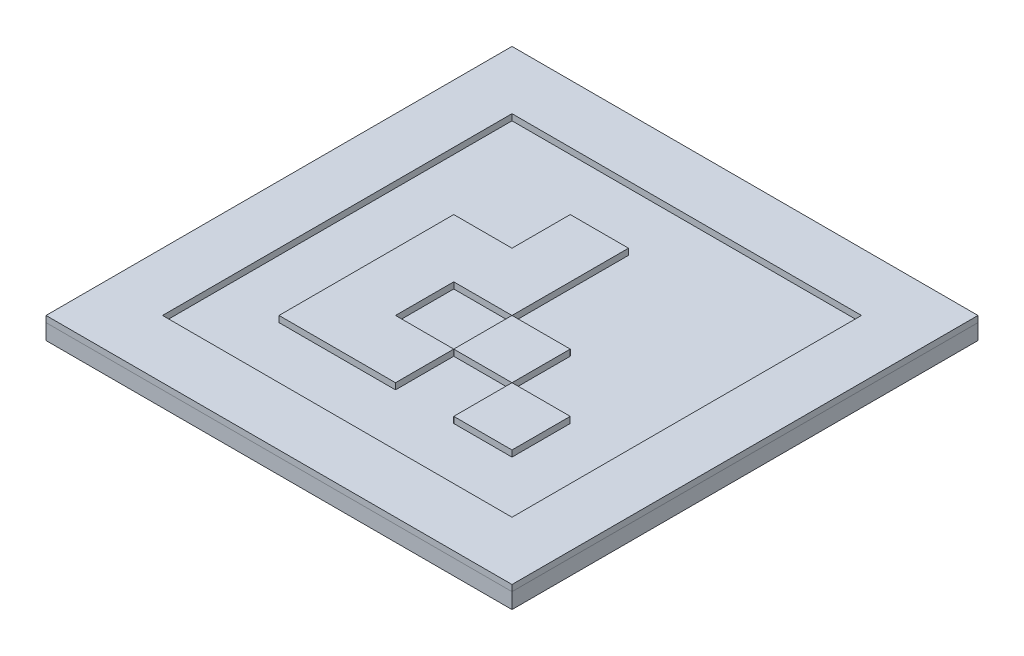
SolidWorks part; units mm, degrees
ref_plane "Спереди" through (0, 0, 0) normal (0, 0, 1) x (1, 0, 0)
ref_plane "Сверху" through (0, 0, 0) normal (0, 1, 0) x (1, 0, 0)
ref_plane "Справа" through (0, 0, 0) normal (1, 0, 0) x (0, 0, -1)
sketch "Эскиз1" plane through (0, 0, 0) normal (0, 1, 0) x (1, 0, 0)
  line L1 (-75, -75) -> (75, -75)
  line L2 (-75, -75) -> (-75, 75)
  line L3 (-75, 75) -> (75, 75)
  line L4 (75, -75) -> (75, 75)
  line L5 (-75, -75) -> (75, 75) construction
  line L6 (-75, 75) -> (75, -75) construction
  point P0 (0, 0)
  dimension "D1" = 150
extrude "Бобышка-Вытянуть1" add sketch "Эскиз1" along normal blind 5
sketch "Эскиз10" plane through (0, 5, 0) normal (0, 1, 0) x (1, 0, 0)
  line L0 (37.5, -37.5) -> (37.5, 37.5)
  line L1 (37.5, 37.5) -> (-37.5, 37.5)
  line L2 (-37.5, 37.5) -> (-37.5, -37.5)
  line L3 (-37.5, -37.5) -> (37.5, -37.5)
  line L4 (75, -75) -> (75, 75)
  line L5 (75, 75) -> (-75, 75)
  line L6 (-75, 75) -> (-75, -75)
  line L7 (-75, -75) -> (75, -75)
  line L8 (75, -75) -> (75, 75) construction
  line L9 (75, 75) -> (-75, 75) construction
  line L10 (-75, 75) -> (-75, -75) construction
  line L11 (-75, -75) -> (75, -75) construction
  line L12 (-18.75, 37.5) -> (-18.75, 18.75)
  line L13 (-37.5, 37.5) -> (-18.75, 37.5)
  line L14 (-37.5, 37.5) -> (-37.5, 18.75)
  line L15 (-37.5, 18.75) -> (-18.75, 18.75)
  line L16 (56.25, -56.25) -> (56.25, 56.25)
  line L17 (56.25, 56.25) -> (-56.25, 56.25)
  line L18 (-56.25, 56.25) -> (-56.25, -56.25)
  line L19 (-56.25, -56.25) -> (56.25, -56.25)
  line L20 (56.25, -56.25) -> (56.25, 56.25)
  line L21 (56.25, 56.25) -> (-56.25, 56.25)
  line L22 (-56.25, 56.25) -> (-56.25, -56.25)
  line L23 (-56.25, -56.25) -> (56.25, -56.25)
  line L24 (-18.75, 37.5) -> (-18.75, 18.75)
  line L25 (-18.75, 37.5) -> (0, 37.5)
  line L26 (0, 37.5) -> (0, 18.75)
  line L27 (-18.75, 18.75) -> (0, 18.75)
  line L28 (0, 37.5) -> (0, 18.75)
  line L29 (0, 37.5) -> (18.75, 37.5)
  line L30 (18.75, 37.5) -> (18.75, 18.75)
  line L31 (0, 18.75) -> (18.75, 18.75)
  line L32 (18.75, 37.5) -> (18.75, 18.75)
  line L33 (18.75, 37.5) -> (37.5, 37.5)
  line L34 (37.5, 37.5) -> (37.5, 18.75)
  line L35 (18.75, 18.75) -> (37.5, 18.75)
  line L36 (-18.75, 18.75) -> (-18.75, 0)
  line L37 (-18.75, 18.75) -> (0, 18.75)
  line L38 (0, 18.75) -> (0, 0)
  line L39 (-18.75, 0) -> (0, 0)
  line L40 (0, 18.75) -> (0, 0)
  line L41 (0, 18.75) -> (18.75, 18.75)
  line L42 (18.75, 18.75) -> (18.75, 0)
  line L43 (0, 0) -> (18.75, 0)
  line L44 (18.75, 18.75) -> (18.75, 0)
  line L45 (18.75, 18.75) -> (37.5, 18.75)
  line L46 (37.5, 18.75) -> (37.5, 0)
  line L47 (18.75, 0) -> (37.5, 0)
  line L48 (-18.75, 0) -> (-18.75, -18.75)
  line L49 (-18.75, 0) -> (0, 0)
  line L50 (0, 0) -> (0, -18.75)
  line L51 (-18.75, -18.75) -> (0, -18.75)
  line L52 (0, 0) -> (0, -18.75)
  line L53 (0, 0) -> (18.75, 0)
  line L54 (18.75, 0) -> (18.75, -18.75)
  line L55 (0, -18.75) -> (18.75, -18.75)
  line L56 (18.75, 0) -> (18.75, -18.75)
  line L57 (18.75, 0) -> (37.5, 0)
  line L58 (37.5, 0) -> (37.5, -18.75)
  line L59 (18.75, -18.75) -> (37.5, -18.75)
  line L60 (-18.75, -18.75) -> (-18.75, -37.5)
  line L61 (-18.75, -18.75) -> (0, -18.75)
  line L62 (0, -18.75) -> (0, -37.5)
  line L63 (-18.75, -37.5) -> (0, -37.5)
  line L64 (0, -18.75) -> (0, -37.5)
  line L65 (0, -18.75) -> (18.75, -18.75)
  line L66 (18.75, -18.75) -> (18.75, -37.5)
  line L67 (0, -37.5) -> (18.75, -37.5)
  line L68 (18.75, -18.75) -> (18.75, -37.5)
  line L69 (18.75, -18.75) -> (37.5, -18.75)
  line L70 (37.5, -18.75) -> (37.5, -37.5)
  line L71 (18.75, -37.5) -> (37.5, -37.5)
  line L72 (-37.5, 18.75) -> (-37.5, 0)
  line L73 (-37.5, 18.75) -> (-18.75, 18.75)
  line L74 (-18.75, 18.75) -> (-18.75, 0)
  line L75 (-37.5, 0) -> (-18.75, 0)
  line L76 (-37.5, 0) -> (-37.5, -18.75)
  line L77 (-37.5, 0) -> (-18.75, 0)
  line L78 (-18.75, 0) -> (-18.75, -18.75)
  line L79 (-37.5, -18.75) -> (-18.75, -18.75)
  line L80 (-37.5, -18.75) -> (-37.5, -37.5)
  line L81 (-37.5, -18.75) -> (-18.75, -18.75)
  line L82 (-18.75, -18.75) -> (-18.75, -37.5)
  line L83 (-37.5, -37.5) -> (-18.75, -37.5)
  line M57 (75, -75) -> (75, 75)
  line M58 (75, 75) -> (-75, 75)
  line M59 (-75, 75) -> (-75, -75)
  line M60 (-75, -75) -> (75, -75)
  dimension "D4" = 18.75
  dimension "D1" = 0
  dimension "D2" = 18.75
  dimension "D3" = 18.75
  dimension "D5" = 4
  dimension "D6" = 4
extrude "Бобышка-Вытянуть8" add sketch "Эскиз10" along normal blind 2 separate body contours L23 L22 L21 L20 M60 M57 M58 M59 | L59 L66 L3 L0 | L50 L55 L54 L43 | L62 L51 L60 L3 | L79 L2 L3 L60 | L2 L79 L48 L75 | L2 L75 L36 L15 | L36 L39 L38 L27 | L12 L27 L26 L1
sketch "Эскиз6" plane through (0, 5, 0) normal (0, 1, 0) x (1, 0, 0)
  line L0 (61.95, -70.05) -> (61.95, -64.45) construction
  line L1 (72.55, -70.05) -> (61.95, -70.05) construction
  line L2 (72.55, -64.45) -> (72.55, -70.05) construction
  line L3 (61.95, -64.45) -> (72.55, -64.45) construction
  line L4 (-61.95, -64.45) -> (-61.95, -70.05) construction
  line L5 (-61.95, -70.05) -> (-72.55, -70.05) construction
  line L6 (-72.55, -70.05) -> (-72.55, -64.45) construction
  line L7 (-72.55, -64.45) -> (-61.95, -64.45) construction
  line L8 (-61.95, 70.05) -> (-61.95, 64.45) construction
  line L9 (-72.55, 70.05) -> (-61.95, 70.05) construction
  line L10 (-72.55, 64.45) -> (-72.55, 70.05) construction
  line L11 (-61.95, 64.45) -> (-72.55, 64.45) construction
  line L12 (72.55, 70.05) -> (72.55, 64.45) construction
  line L13 (72.55, 64.45) -> (61.95, 64.45) construction
  line L14 (61.95, 64.45) -> (61.95, 70.05) construction
  line L15 (61.95, 70.05) -> (72.55, 70.05) construction
  line L16 (61.95, -70.05) -> (61.95, -64.45)
  line L17 (72.55, -70.05) -> (61.95, -70.05)
  line L18 (72.55, -64.45) -> (72.55, -70.05)
  line L19 (61.95, -64.45) -> (72.55, -64.45)
  line L20 (-61.95, -64.45) -> (-61.95, -70.05)
  line L21 (-61.95, -70.05) -> (-72.55, -70.05)
  line L22 (-72.55, -70.05) -> (-72.55, -64.45)
  line L23 (-72.55, -64.45) -> (-61.95, -64.45)
  line L24 (-61.95, 70.05) -> (-61.95, 64.45)
  line L25 (-72.55, 70.05) -> (-61.95, 70.05)
  line L26 (-72.55, 64.45) -> (-72.55, 70.05)
  line L27 (-61.95, 64.45) -> (-72.55, 64.45)
  line L28 (72.55, 70.05) -> (72.55, 64.45)
  line L29 (72.55, 64.45) -> (61.95, 64.45)
  line L30 (61.95, 64.45) -> (61.95, 70.05)
  line L31 (61.95, 70.05) -> (72.55, 70.05)
extrude "Вырез-Вытянуть1" cut sketch "Эскиз6" against normal blind 4
sketch "Эскиз7" plane through (0, 5, 0) normal (0, 1, 0) x (1, 0, 0)
  line L0 (61.95, -70.05) -> (72.55, -70.05) construction
  line L1 (72.55, -70.05) -> (72.55, -64.45) construction
  line L2 (72.55, -64.45) -> (61.95, -64.45) construction
  line L3 (61.95, -64.45) -> (61.95, -70.05) construction
  line L4 (-61.95, -64.45) -> (-72.55, -64.45) construction
  line L5 (-72.55, -64.45) -> (-72.55, -70.05) construction
  line L6 (-72.55, -70.05) -> (-61.95, -70.05) construction
  line L7 (-61.95, -70.05) -> (-61.95, -64.45) construction
  line L8 (72.55, 70.05) -> (61.95, 70.05) construction
  line L9 (61.95, 70.05) -> (61.95, 64.45) construction
  line L10 (61.95, 64.45) -> (72.55, 64.45) construction
  line L11 (72.55, 64.45) -> (72.55, 70.05) construction
  line L12 (-61.95, 70.05) -> (-72.55, 70.05) construction
  line L13 (-72.55, 70.05) -> (-72.55, 64.45) construction
  line L14 (-72.55, 64.45) -> (-61.95, 64.45) construction
  line L15 (-61.95, 64.45) -> (-61.95, 70.05) construction
  line L16 (61.95, -70.05) -> (72.55, -70.05)
  line L17 (72.55, -70.05) -> (72.55, -64.45)
  line L18 (72.55, -64.45) -> (61.95, -64.45)
  line L19 (61.95, -64.45) -> (61.95, -70.05)
  line L20 (-61.95, -64.45) -> (-72.55, -64.45)
  line L21 (-72.55, -64.45) -> (-72.55, -70.05)
  line L22 (-72.55, -70.05) -> (-61.95, -70.05)
  line L23 (-61.95, -70.05) -> (-61.95, -64.45)
  line L24 (72.55, 70.05) -> (61.95, 70.05)
  line L25 (61.95, 70.05) -> (61.95, 64.45)
  line L26 (61.95, 64.45) -> (72.55, 64.45)
  line L27 (72.55, 64.45) -> (72.55, 70.05)
  line L28 (-61.95, 70.05) -> (-72.55, 70.05)
  line L29 (-72.55, 70.05) -> (-72.55, 64.45)
  line L30 (-72.55, 64.45) -> (-61.95, 64.45)
  line L31 (-61.95, 64.45) -> (-61.95, 70.05)
extrude "Бобышка-Вытянуть7" add sketch "Эскиз7" against normal blind 1
